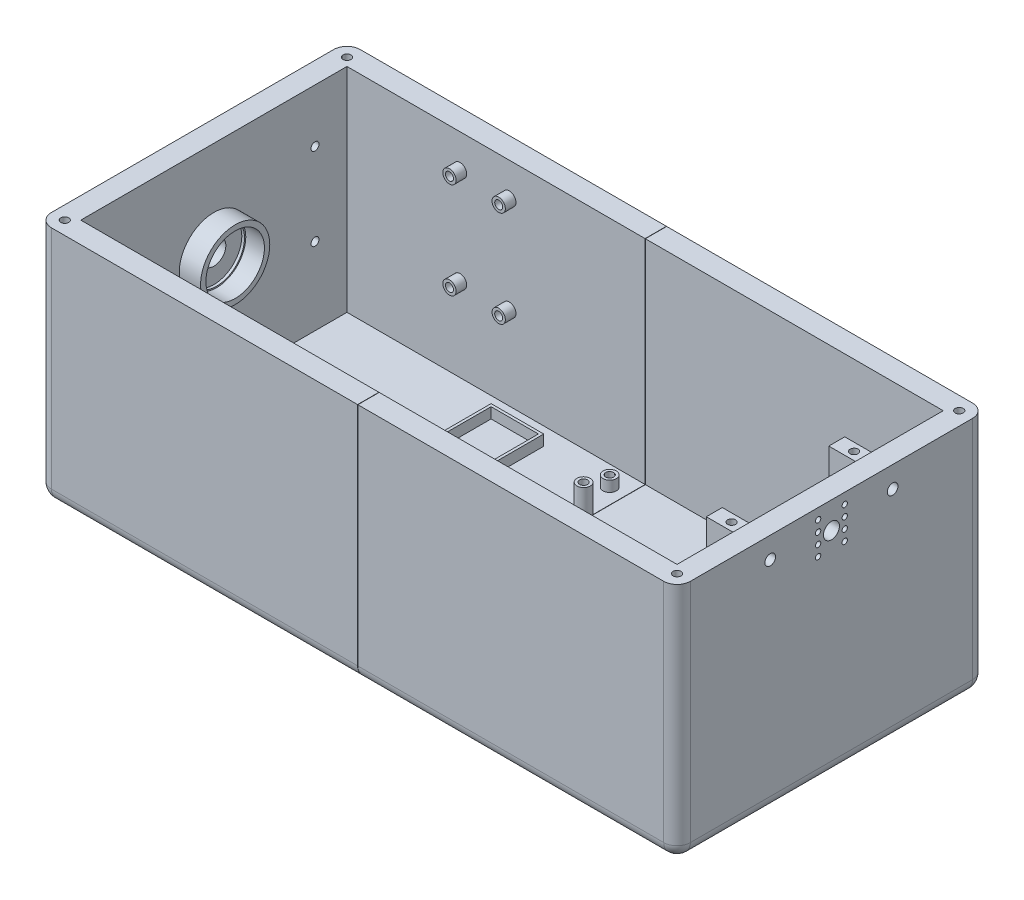
SolidWorks part; units mm, degrees
ref_plane "Front Plane" through (0, 0, 0) normal (0, 0, 1) x (1, 0, 0)
ref_plane "Top Plane" through (0, 0, 0) normal (0, 1, 0) x (1, 0, 0)
ref_plane "Right Plane" through (0, 0, 0) normal (1, 0, 0) x (0, 0, -1)
sketch "Sketch1" plane through (0, 0, 0) normal (0, 1, 0) x (1, 0, 0)
  line L1 (-120, 58) -> (120, 58)
  line L2 (-120, 58) -> (-120, -58)
  line L3 (-120, -58) -> (120, -58)
  line L4 (120, 58) -> (120, -58)
  line L5 (-120, 58) -> (120, -58) construction
  line L6 (-120, -58) -> (120, 58) construction
  point P0 (0, 0)
  dimension "D1" = 240
  dimension "D2" = 116
extrude "Boss-Extrude1" add sketch "Sketch1" along normal blind 10
sketch "Sketch2" plane through (0, 0, 0) normal (0, -1, 0) x (1, 0, 0)
  line L1 (-31.075, 31.075) -> (31.075, 31.075)
  line L2 (-31.075, 31.075) -> (-31.075, -31.075)
  line L3 (-31.075, -31.075) -> (31.075, -31.075)
  line L4 (31.075, 31.075) -> (31.075, -31.075)
  line L5 (-31.075, 31.075) -> (31.075, -31.075) construction
  line L6 (-31.075, -31.075) -> (31.075, 31.075) construction
  point P0 (0, 0)
  dimension "D1" = 62.15
  dimension "D2" = 62.15
extrude "Cut-Extrude1" cut sketch "Sketch2" against normal blind 2.5
sketch "Sketch3" plane through (0, 2.5, 0) normal (0, -1, 0) x (1, 0, 0)
  line L0 (0, 31.075) -> (0, -31.075) construction
  line L1 (31.075, 31.075) -> (-31.075, 31.075) construction
  line L2 (-31.075, -31.075) -> (31.075, -31.075) construction
  line L3 (-31.075, 0) -> (31.075, 0) construction
  line L4 (-31.075, 31.075) -> (-31.075, -31.075) construction
  line L5 (31.075, -31.075) -> (31.075, 31.075) construction
  line L6 (31.075, 31.075) -> (-31.075, 31.075) construction
  line L7 (-31.075, 31.075) -> (-31.075, -31.075) construction
  circle A0 centre (-26.075, 26.075) radius 1.5
  circle A1 centre (-26.075, -26.075) radius 1.5
  circle A2 centre (26.075, -26.075) radius 1.5
  circle A3 centre (26.075, 26.075) radius 1.5
  dimension "D1" = 3
  dimension "D3" = 5
  dimension "D2" = 5
extrude "Cut-Extrude2" cut sketch "Sketch3" against normal up to next
sketch "Sketch4" plane through (0, 0, 0) normal (0, -1, 0) x (1, 0, 0)
  line L0 (120, 58) -> (120, -58) construction
  line L1 (48, 7.75) -> (60, 7.75)
  line L2 (48, 7.75) -> (48, -7.75)
  line L3 (48, -7.75) -> (60, -7.75)
  line L4 (60, 7.75) -> (60, -7.75)
  line L5 (48, 7.75) -> (60, -7.75) construction
  line L6 (48, -7.75) -> (60, 7.75) construction
  point P0 (54, 0)
  dimension "D1" = 12
  dimension "D2" = 15.5
  dimension "D3" = 60
extrude "Cut-Extrude3" cut sketch "Sketch4" against normal blind 2.5
sketch "Sketch6" plane through (0, 2.5, 0) normal (0, -1, 0) x (1, 0, 0)
  line L0 (60, -7.75) -> (60, 7.75) construction
  line L1 (60, 7.75) -> (48, 7.75) construction
  line L2 (48, -7.75) -> (60, -7.75) construction
  circle A0 centre (58, 5.75) radius 1.5
  circle A1 centre (58, -5.75) radius 1.5
  dimension "D1" = 3
  dimension "D2" = 3
  dimension "D3" = 2
  dimension "D4" = 2
  dimension "D5" = 2
  dimension "D6" = 2
extrude "Cut-Extrude4" cut sketch "Sketch6" against normal up to next and the other way through all
sketch "Sketch7" plane through (0, 2.5, 0) normal (0, -1, 0) x (1, 0, 0)
  line L0 (48, -7.75) -> (60, -7.75) construction
  line L1 (48, 7.75) -> (54, 7.75)
  line L2 (48, 7.75) -> (48, -7.75)
  line L3 (48, -7.75) -> (54, -7.75)
  line L4 (54, 7.75) -> (54, -7.75)
extrude "Cut-Extrude5" cut sketch "Sketch7" against normal up to next
sketch "Sketch8" plane through (0, 10, 0) normal (0, 1, 0) x (1, 0, 0)
  line L1 (1.2, 26.7) -> (100, 26.7) construction
  line L2 (1.2, 26.7) -> (1.2, -26.7) construction
  line L3 (1.2, -26.7) -> (100, -26.7) construction
  line L4 (100, 26.7) -> (100, -26.7) construction
  line L5 (1.2, 26.7) -> (100, -26.7) construction
  line L6 (1.2, -26.7) -> (100, 26.7) construction
  line L11 (120, -58) -> (120, 58) construction
  line L15 (-120, -58) -> (120, -58) construction
  circle A0 centre (2.7, 24.2) radius 1.5
  circle A1 centre (9.7, -24.2) radius 1.5
  circle A2 centre (86.5, 24.2) radius 1.5
  circle A3 centre (84.5, -24.2) radius 1.5
  circle A4 centre (86.5, 24.2) radius 2.5
  circle A5 centre (84.5, -24.2) radius 2.3473
  circle A6 centre (9.7, -24.2) radius 2.5
  circle A7 centre (2.7, 24.2) radius 2.5
  point P0 (50.6, 0)
  dimension "D7" = 3
  dimension "D8" = 3
  dimension "D9" = 3
  dimension "D10" = 3
  dimension "D11" = 2.5
  dimension "D13" = 8.5
  dimension "D14" = 2.5
  dimension "D12" = 15.5
  dimension "D16" = 13.5
  dimension "D17" = 2.5
  dimension "D18" = 5
  dimension "D19" = 5
  dimension "D20" = 5
  dimension "D1" = 98.8
  dimension "D2" = 53.4
  dimension "D3" = 20
  dimension "D4" = 58
  dimension "D15" = 2.5
extrude "Boss-Extrude2" add sketch "Sketch8" along normal blind 15
sketch "Sketch9" plane through (0, 10, 0) normal (0, 1, 0) x (1, 0, 0)
  line L0 (-0.3, 58) -> (-0.3, -58) construction
  line L1 (-25.6, 47) -> (-4.3, 47) construction
  line L2 (-25.6, 47) -> (-25.6, 8.5) construction
  line L3 (-25.6, 8.5) -> (-4.3, 8.5) construction
  line L4 (-4.3, 47) -> (-4.3, 8.5) construction
  line L5 (-25.6, 47) -> (-4.3, 8.5) construction
  line L6 (-25.6, 8.5) -> (-4.3, 47) construction
  line L7 (-53.1, 47) -> (-29.6, 47) construction
  line L8 (-53.1, 47) -> (-53.1, 5) construction
  line L9 (-53.1, 5) -> (-29.6, 5) construction
  line L10 (-29.6, 47) -> (-29.6, 5) construction
  line L11 (-53.1, 47) -> (-29.6, 5) construction
  line L12 (-53.1, 5) -> (-29.6, 47) construction
  line L13 (120, 58) -> (-120, 58) construction
  line L14 (-120, -58) -> (120, -58) construction
  line L15 (-76.2, -9.5) -> (-54.9, -9.5) construction
  line L16 (-103.7, -9) -> (-80.2, -9) construction
  line L17 (-17.7, -47) -> (-17.7, -48)
  line L18 (-21.7, -23.8) -> (-4.3, -23.8)
  line L19 (-21.7, -23.8) -> (-21.7, -47)
  line L20 (-21.7, -47) -> (-17.7, -47)
  line L21 (-4.3, -23.8) -> (-4.3, -47)
  line L22 (-21.7, -23.8) -> (-4.3, -47) construction
  line L23 (-21.7, -47) -> (-4.3, -23.8) construction
  line L24 (-22.7, -22.8) -> (-3.3, -22.8)
  line L25 (-22.7, -22.8) -> (-22.7, -48)
  line L26 (-22.7, -48) -> (-17.7, -48)
  line L27 (-3.3, -22.8) -> (-3.3, -48)
  line L28 (-22.7, -22.8) -> (-3.3, -48) construction
  line L29 (-22.7, -48) -> (-3.3, -22.8) construction
  line L30 (-8.3, -47) -> (-8.3, -48)
  line L31 (-8.3, -47) -> (-4.3, -47)
  line L32 (-8.3, -48) -> (-3.3, -48)
  line L51 (-31.46, 43.383) -> (-31.46, 8.617)
  line L52 (-50.24, 42.383) -> (-32.46, 42.383)
  line L53 (-50.24, 42.383) -> (-50.24, 9.617)
  line L54 (-50.24, 9.617) -> (-32.46, 9.617)
  line L67 (31.45, 58) -> (31.45, -58) construction
  line L102 (-32.46, 42.383) -> (-32.46, 9.617)
  line L103 (-50.24, 42.383) -> (-32.46, 9.617) construction
  line L104 (-50.24, 9.617) -> (-32.46, 42.383) construction
  line L105 (-51.24, 8.617) -> (-31.46, 8.617)
  line L106 (-51.24, 43.383) -> (-51.24, 8.617)
  line L107 (-51.24, 43.383) -> (-31.46, 43.383)
  circle A0 centre (2.7, 24.2) radius 1.5 construction
  circle A1 centre (-5.8, 42.5) radius 1.5
  circle A2 centre (-5.8, 15.8) radius 1.5
  circle A3 centre (-24.1, 15.8) radius 1.5
  circle A4 centre (-24.1, 15.8) radius 2.5
  circle A5 centre (-5.8, 15.8) radius 2.5
  circle A6 centre (-5.8, 42.5) radius 2.5
  circle A7 centre (-50.6, 44.5) radius 1.5 construction
  circle A8 centre (-32.1, 44.5) radius 1.5 construction
  circle A9 centre (-32.1, 7.5) radius 1.5 construction
  circle A10 centre (-50.6, 7.5) radius 1.5 construction
  circle A11 centre (-50.6, 7.5) radius 2.5 construction
  circle A12 centre (-32.1, 7.5) radius 2.5 construction
  circle A13 centre (-32.1, 44.5) radius 2.5 construction
  circle A14 centre (-50.6, 44.5) radius 2.5 construction
  point P0 (-14.95, 27.75)
  point P5 (-41.35, 26)
  point P20 (-13, -35.4)
  point P27 (-13, -35.4)
  point P53 (-41.35, 26)
  dimension "D23" = 3
  dimension "D24" = 3
  dimension "D25" = 3
  dimension "D28" = 5
  dimension "D29" = 5
  dimension "D30" = 5
  dimension "D31" = 3
  dimension "D32" = 3
  dimension "D33" = 3
  dimension "D34" = 3
  dimension "D43" = 5
  dimension "D44" = 5
  dimension "D45" = 5
  dimension "D46" = 5
  dimension "D1" = 38.5
  dimension "D2" = 21.3
  dimension "D3" = 3
  dimension "D4" = 4
  dimension "D5" = 18
  dimension "D6" = 42
  dimension "D7" = 23.5
  dimension "D8" = 4
  dimension "D9" = 11
  dimension "D10" = 14
  dimension "D11" = 17.4
  dimension "D12" = 23.2
  dimension "D14" = 4
  dimension "D15" = 25.2
  dimension "D16" = 19.4
  dimension "D17" = 4
  dimension "D22" = 4.5
  dimension "D26" = 7.3
  dimension "D27" = 7.3
  dimension "D35" = 2.5
  dimension "D36" = 2.5
  dimension "D37" = 2.5
  dimension "D38" = 2.5
  dimension "D39" = 2.5
  dimension "D40" = 2.5
  dimension "D41" = 2.5
  dimension "D42" = 2.5
  dimension "D47" = 32.766
  dimension "D48" = 17.78
  dimension "D49" = 1
extrude "Boss-Extrude3" add sketch "Sketch9" along normal blind 4
sketch "Sketch10" plane through (0, 10, 0) normal (0, 1, 0) x (1, 0, 0)
  line L0 (-112, 50) -> (112, 50)
  line L1 (-120, 58) -> (120, 58)
  line L2 (-120, 58) -> (-120, -58)
  line L3 (-120, -58) -> (120, -58)
  line L4 (120, 58) -> (120, -58)
  line L5 (-120, 58) -> (120, -58) construction
  line L6 (-120, -58) -> (120, 58) construction
  line L7 (112, 50) -> (112, -50)
  line L8 (-112, -50) -> (112, -50)
  line L9 (-112, 50) -> (-112, -50)
  point P0 (0, 0)
  dimension "D1" = 8
extrude "Boss-Extrude4" add sketch "Sketch10" along normal blind 80
sketch "Sketch11" plane through (112, 0, 0) normal (-1, 0, 0) x (0, 0, 1)
  line L0 (-50, 90) -> (-50, 10) construction
  line L1 (-37, 82.5) -> (23, 82.5) construction
  line L2 (-37, 82.5) -> (-37, 17.5) construction
  line L3 (-37, 17.5) -> (23, 17.5) construction
  line L4 (23, 82.5) -> (23, 17.5) construction
  line L5 (-37, 82.5) -> (23, 17.5) construction
  line L6 (-37, 17.5) -> (23, 82.5) construction
  line L7 (-27.9, 70.9) -> (13.9, 70.9) construction
  line L8 (-27.9, 70.9) -> (-27.9, 29.1) construction
  line L9 (-27.9, 29.1) -> (13.9, 29.1) construction
  line L10 (13.9, 70.9) -> (13.9, 29.1) construction
  line L11 (-27.9, 70.9) -> (13.9, 29.1) construction
  line L12 (-27.9, 29.1) -> (13.9, 70.9) construction
  line L15 (50, 90) -> (-50, 90) construction
  circle A0 centre (-22.9, 65.9) radius 1.5
  circle A1 centre (8.9, 65.9) radius 1.5
  circle A2 centre (8.9, 34.1) radius 1.5
  circle A3 centre (-22.9, 34.1) radius 1.5
  circle A4 centre (-7, 67.5) radius 4.5
  point P0 (-7, 50)
  point P6 (-7, 50)
  dimension "D5" = 3
  dimension "D6" = 3
  dimension "D8" = 3
  dimension "D7" = 3
  dimension "D19" = 9
  dimension "D1" = 65
  dimension "D2" = 60
  dimension "D3" = 41.8
  dimension "D4" = 41.8
  dimension "D10" = 5
  dimension "D11" = 5
  dimension "D12" = 5
  dimension "D13" = 5
  dimension "D14" = 5
  dimension "D15" = 5
  dimension "D16" = 5
  dimension "D17" = 43
  dimension "D18" = 40
  dimension "D20" = 15
  dimension "D21" = 30
  dimension "D9" = 5
extrude "Cut-Extrude6" [suppressed] cut sketch "Sketch11" against normal up to next contours A1 | A3 | A2 | A0
sketch "Sketch13" [suppressed] plane through (120, 0, 0) normal (1, 0, 0) x (0, 0, -1)
  circle A0 centre (-8.9, 65.9) radius 3
  circle A1 centre (22.9, 65.9) radius 3
  circle A2 centre (22.9, 34.1) radius 3
  circle A3 centre (-8.9, 34.1) radius 3
  dimension "D1" = 6
  dimension "D2" = 6
  dimension "D3" = 6
  dimension "D4" = 6
extrude "Cut-Extrude7" [suppressed] cut sketch "Sketch13" against normal blind 4
sketch "Sketch24" plane through (-112, 0, 0) normal (1, 0, 0) x (0, 0, -1)
  line L0 (50, 10) -> (-50, 10) construction
  line L1 (-43, 34) -> (43, 34) construction
  line L2 (-43, 34) -> (-43, 75) construction
  line L3 (-43, 75) -> (43, 75) construction
  line L4 (43, 34) -> (43, 75) construction
  line L5 (-43, 34) -> (43, 75) construction
  line L6 (-43, 75) -> (43, 34) construction
  line L7 (50, 90) -> (-50, 90) construction
  line L8 (0, 75) -> (0, 34) construction
  circle A0 centre (-38, 70) radius 1.5
  circle A1 centre (-38, 39) radius 1.5
  circle A2 centre (38, 39) radius 1.5
  circle A3 centre (38, 70) radius 1.5
  point P0 (0, 54.5)
  point P9 (0, 10)
  dimension "D4" = 3
  dimension "D5" = 3
  dimension "D6" = 5
  dimension "D7" = 5
  dimension "D8" = 5
  dimension "D9" = 5
  dimension "D1" = 86
  dimension "D2" = 41
  dimension "D3" = 15
extrude "Cut-Extrude14" cut sketch "Sketch24" against normal up to next
sketch "Sketch14" plane through (-112, 0, 0) normal (1, 0, 0) x (0, 0, -1)
  circle A0 centre (0, 54.5) radius 13
  circle A2 centre (0, 54.5) radius 11
  dimension "D1" = 26
  dimension "D2" = 22
  dimension "D3" = 0
extrude "Boss-Extrude6" add sketch "Sketch14" along normal blind 8
sketch "Sketch16" plane through (-112, 0, 0) normal (1, 0, 0) x (0, 0, -1)
  circle A0 centre (0, 54.5) radius 10.5
  circle A1 centre (0, 54.5) radius 11
  dimension "D1" = 21
  dimension "D2" = 22
extrude "Boss-Extrude7" add sketch "Sketch16" along normal blind 1
sketch "Sketch18" plane through (0, 0, -50) normal (0, 0, 1) x (1, 0, 0)
  line L0 (-60.25, 80) -> (-60.25, 38) construction
  line L1 (-72, 80) -> (-48.5, 80) construction
  line L2 (-72, 80) -> (-72, 38) construction
  line L3 (-72, 38) -> (-48.5, 38) construction
  line L4 (-48.5, 80) -> (-48.5, 38) construction
  line L5 (-72, 80) -> (-48.5, 38) construction
  line L6 (-72, 38) -> (-48.5, 80) construction
  line L7 (-72, 59.4256) -> (-48.5, 59.4256) construction
  line L8 (112, 90) -> (-112, 90) construction
  line L9 (-112, 90) -> (-112, 10) construction
  circle A0 centre (-69.5, 77.5) radius 1.5
  circle A1 centre (-69.5, 77.5) radius 2.5
  circle A2 centre (-69.5, 41.3512) radius 1.5
  circle A3 centre (-69.5, 41.3512) radius 2.5
  circle A4 centre (-51, 41.3512) radius 2.5
  circle A5 centre (-51, 41.3512) radius 1.5
  circle A6 centre (-51, 77.5) radius 2.5
  circle A7 centre (-51, 77.5) radius 1.5
  point P0 (-60.25, 59)
  dimension "D3" = 3
  dimension "D4" = 5
  dimension "D5" = 2.5
  dimension "D6" = 2.5
  dimension "D1" = 42
  dimension "D2" = 23.5
  dimension "D7" = 10
  dimension "D8" = 40
sketch "Sketch17" plane through (-112, 0, 0) normal (1, 0, 0) x (0, 0, -1)
  circle A0 centre (0, 54.5) radius 4.5
  dimension "D1" = 9
extrude "Cut-Extrude9" cut sketch "Sketch17" against normal up to next
extrude "Boss-Extrude8" add sketch "Sketch18" along normal blind 4
fillet "Fillet1" radius 5 8 edges at (120, 45, -58) (-120, 45, -58) (0, 0, -58) (-120, 0, 0) (0, 0, 58) (-120, 45, 58) (120, 0, 0) (120, 45, 58)
sketch "Sketch19" plane through (0, 90, 0) normal (0, 1, 0) x (1, 0, 0)
  circle A3 centre (115, 53) radius 1.5
  circle A4 centre (-115, 53) radius 1.5
  circle A5 centre (-115, -53) radius 1.5
  circle A6 centre (115, -53) radius 1.5
  dimension "D1" = 3
  dimension "D2" = 3
  dimension "D3" = 3
  dimension "D4" = 3
extrude "Cut-Extrude10" cut sketch "Sketch19" against normal blind 20
sketch "Sketch20" plane through (120, 0, 0) normal (1, 0, 0) x (0, 0, -1)
  line L0 (0, 90) -> (0, 0) construction
  line L1 (-53, 90) -> (53, 90) construction
  circle A0 centre (-23, 82) radius 2
  circle A1 centre (23, 82) radius 2
  dimension "D1" = 23
  dimension "D2" = 4
  dimension "D3" = 8
extrude "Cut-Extrude11" cut sketch "Sketch20" against normal up to next
sketch "Sketch21" plane through (112, 0, 0) normal (-1, 0, 0) x (0, 0, 1)
  line L1 (-26, 87) -> (-20, 87)
  line L2 (-26, 87) -> (-26, 77)
  line L3 (-26, 77) -> (-20, 77)
  line L4 (-20, 87) -> (-20, 77)
  line L5 (-26, 87) -> (-20, 77) construction
  line L6 (-26, 77) -> (-20, 87) construction
  line L7 (20, 87) -> (26, 87)
  line L8 (20, 87) -> (20, 77)
  line L9 (20, 77) -> (26, 77)
  line L10 (26, 87) -> (26, 77)
  line L11 (20, 87) -> (26, 77) construction
  line L12 (20, 77) -> (26, 87) construction
  circle A0 centre (23, 82) radius 2
  circle A1 centre (-23, 82) radius 2
  point P0 (-23, 82)
  point P6 (23, 82)
  dimension "D5" = 4
  dimension "D6" = 4
  dimension "D1" = 6
  dimension "D2" = 6
  dimension "D3" = 10
  dimension "D4" = 10
extrude "Boss-Extrude9" add sketch "Sketch21" along normal blind 13
sketch "Sketch22" plane through (0, 87, 0) normal (0, 1, 0) x (1, 0, 0)
  line L0 (99, -26) -> (99, -20) construction
  line L1 (99, -20) -> (112, -20) construction
  line L2 (99, 20) -> (99, 26) construction
  line L3 (99, 26) -> (112, 26) construction
  circle A0 centre (105.5, -23) radius 1.5
  circle A1 centre (105.5, 23) radius 1.5
  dimension "D1" = 3
  dimension "D2" = 6.5
  dimension "D3" = 3
  dimension "D4" = 3
  dimension "D5" = 6.5
  dimension "D6" = 3
extrude "Cut-Extrude12" cut sketch "Sketch22" against normal up to next
sketch "Sketch23" plane through (120, 0, 0) normal (1, 0, 0) x (0, 0, -1)
  line L0 (0, 90) -> (0, 5) construction
  line L1 (-53, 90) -> (53, 90) construction
  line L2 (-53, 5) -> (53, 5) construction
  line L3 (-9.0972, 80) -> (9.0972, 80) construction
  circle A0 centre (5, 78) radius 1
  circle A1 centre (-5, 78) radius 1
  circle A2 centre (5, 74) radius 1
  circle A3 centre (-5, 74) radius 1
  circle A4 centre (-5, 86) radius 1
  circle A5 centre (5, 86) radius 1
  circle A6 centre (-5, 82) radius 1
  circle A7 centre (5, 82) radius 1
  circle A8 centre (0, 80) radius 3
  point P24 (0, 80)
  dimension "D1" = 2
  dimension "D2" = 2
  dimension "D3" = 5
  dimension "D4" = 5
  dimension "D5" = 12
  dimension "D6" = 12
  dimension "D7" = 2
  dimension "D8" = 2
  dimension "D9" = 5
  dimension "D10" = 5
  dimension "D11" = 4
  dimension "D12" = 4
  dimension "D13" = 2
  dimension "D14" = 6
extrude "Cut-Extrude13" cut sketch "Sketch23" against normal up to next
ref_plane "Plane1" through (-120, 0, 0) normal (-1, 0, 0) x (0, 0, 1)
sketch "Sketch25" plane through (-120, 0, 0) normal (-1, 0, 0) x (0, 0, 1)
  line L0 (-53, 90) -> (-53, 5)
  line L1 (53, 5) -> (53, 90)
  line L2 (-53, 90) -> (53, 90)
  line L3 (-53, 5) -> (53, 5)
  line L4 (-53, 5) -> (53, 5)
  line L5 (-53, 90) -> (53, 90)
  line L6 (53, 5) -> (53, 90)
  line L7 (-53, 90) -> (-53, 5)
  circle A0 centre (0, 54.5) radius 4.5
  circle A1 centre (38, 70) radius 1.5
  circle A2 centre (-38, 39) radius 1.5
  circle A3 centre (-38, 70) radius 1.5
  circle A4 centre (38, 39) radius 1.5
  circle A5 centre (38, 39) radius 1.5
  circle A6 centre (-38, 70) radius 1.5
  circle A7 centre (-38, 39) radius 1.5
  circle A8 centre (38, 70) radius 1.5
  circle A9 centre (0, 54.5) radius 4.5
ref_plane "Plane2" through (0, 0, 0) normal (-1, 0, 0) x (0, 0, 1)
sketch "Sketch26" plane through (0, 0, 0) normal (-1, 0, 0) x (0, 0, 1)
  line L0 (-31.075, 0.75) -> (-55.6339, 0.75)
  line L1 (55.6339, 0.75) -> (31.075, 0.75)
  line L2 (-50, 10) -> (-50, 90)
  line L3 (50, 90) -> (50, 10)
  line L4 (-50, 90) -> (-58, 90)
  line L5 (58, 90) -> (50, 90)
  line L6 (-31.075, 2.5) -> (31.075, 2.5)
  line L7 (58, 90) -> (58, 5)
  line L8 (-58, 5) -> (-58, 90)
  line L9 (50, 10) -> (-50, 10)
  line L10 (31.075, 0.75) -> (31.075, 2.5)
  line L11 (-31.075, 2.5) -> (-31.075, 0.75)
  line L12 (-31.075, 2.5) -> (-31.075, 0.75)
  line L13 (31.075, 0.75) -> (31.075, 2.5)
  line L14 (50, 10) -> (-50, 10)
  line L15 (-58, 5) -> (-58, 90)
  line L16 (58, 90) -> (58, 5)
  line L17 (-31.075, 2.5) -> (31.075, 2.5)
  line L18 (58, 90) -> (50, 90)
  line L19 (-50, 90) -> (-58, 90)
  line L20 (50, 90) -> (50, 10)
  line L21 (-50, 10) -> (-50, 90)
  line L22 (55.6339, 0.75) -> (31.075, 0.75)
  line L23 (-31.075, 0.75) -> (-55.6339, 0.75)
  arc A0 (-58, 5) -> (-55.6339, 0.75) centre (-53, 5) ccw
  arc A1 (55.6339, 0.75) -> (58, 5) centre (53, 5) ccw
  arc A2 (55.6339, 0.75) -> (58, 5) centre (53, 5) ccw
  arc A3 (-58, 5) -> (-55.6339, 0.75) centre (-53, 5) ccw
sketch "Sketch27" plane through (0, 0, 0) normal (-1, 0, 0) x (0, 0, 1)
  line L1 (-68.0376, 113.8657) -> (68.0376, 113.8657)
  line L2 (-68.0376, 113.8657) -> (-68.0376, -4.8657)
  line L3 (-68.0376, -4.8657) -> (68.0376, -4.8657)
  line L4 (68.0376, 113.8657) -> (68.0376, -4.8657)
  line L5 (-68.0376, 113.8657) -> (68.0376, -4.8657) construction
  line L6 (-68.0376, -4.8657) -> (68.0376, 113.8657) construction
  point P0 (0, 54.5)
extrude "Cut-Extrude15" cut sketch "Sketch27" against normal blind 0.1
sketch "Sketch28" plane through (0, 0, 0) normal (1, 0, 0) x (0, 0, -1)
  line L0 (53, 0) -> (31.075, 0) construction
  line L1 (58, 5) -> (58, 90) construction
  line L2 (-31.075, 0) -> (-53, 0) construction
  line L3 (-58, 90) -> (-58, 5) construction
  circle A0 centre (-48, 4) radius 2.25
  circle A1 centre (48, 4) radius 2.25
  dimension "D1" = 4.5
  dimension "D2" = 4
  dimension "D3" = 10
  dimension "D4" = 4.5
  dimension "D5" = 4
  dimension "D6" = 10
extrude "Cut-Extrude16" cut sketch "Sketch28" against normal blind 100
equation "\"D2@Sketch2\"=\"D1@Sketch2\""
equation "\"D15@Sketch9\"=\"D12@Sketch9\"+2"
equation "\"D16@Sketch9\"=\"D11@Sketch9\"+2"
equation "\"D17@Sketch11\"=86/2"
equation "\"D18@Sketch11\"=80/2"
